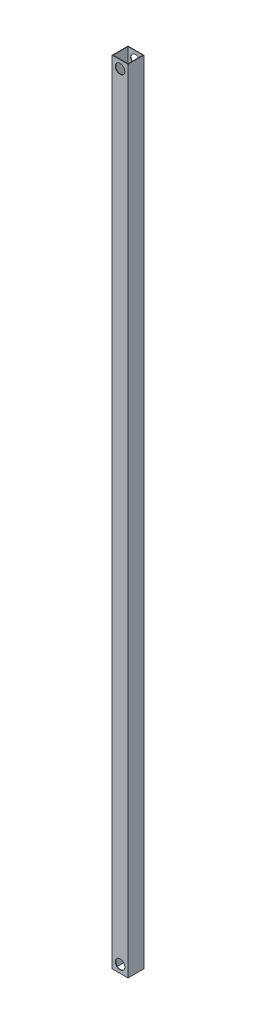
SolidWorks part; units mm, degrees
ref_plane "Alzado" through (0, 0, 0) normal (0, 0, 1) x (1, 0, 0)
ref_plane "Planta" through (0, 0, 0) normal (0, 1, 0) x (1, 0, 0)
ref_plane "Vista lateral" through (0, 0, 0) normal (1, 0, 0) x (0, 0, -1)
sketch "Croquis1" plane through (0, 0, 0) normal (0, 1, 0) x (1, 0, 0)
  line L1 (-5, 5) -> (5, 5)
  line L2 (-5, 5) -> (-5, -5)
  line L3 (-5, -5) -> (5, -5)
  line L4 (5, 5) -> (5, -5)
  line L5 (-5, 5) -> (5, -5) construction
  line L6 (-5, -5) -> (5, 5) construction
  point P0 (0, 0)
  dimension "D1" = 10
  dimension "D2" = 10
extrude "Saliente-Extruir1" add sketch "Croquis1" along normal blind 500
sketch "Croquis2" plane through (0, 500, 0) normal (0, 1, 0) x (1, 0, 0)
  line L0 (-5, 5) -> (-5, -5) construction
  line L1 (-4.683, 4.683) -> (4.683, 4.683)
  line L2 (-4.683, 4.683) -> (-4.683, -4.683)
  line L3 (-4.683, -4.683) -> (4.683, -4.683)
  line L4 (4.683, 4.683) -> (4.683, -4.683)
  line L5 (-4.683, 4.683) -> (4.683, -4.683) construction
  line L6 (-4.683, -4.683) -> (4.683, 4.683) construction
  line L7 (5, 5) -> (-5, 5) construction
  point P0 (0, 0)
  dimension "D1" = 0.317
  dimension "D2" = 0.317
extrude "Cortar-Extruir1" cut sketch "Croquis2" against normal blind 500
sketch "Croquis3" plane through (0, 0, 5) normal (0, 0, 1) x (1, 0, 0)
  line L0 (-5, 10) -> (5, 10) construction
  line L1 (-5, 500) -> (-5, 0) construction
  line L2 (5, 500) -> (5, 0) construction
  line L3 (-5, 0) -> (5, 0) construction
  line L4 (0, 0) -> (0, 10) construction
  line L5 (-5, 5) -> (5, 5) construction
  circle A0 centre (0, 5) radius 3
  dimension "D3" = 6
  dimension "D1" = 10
  dimension "D2" = 5
extrude "Cortar-Extruir2" cut sketch "Croquis3" against normal blind 500
sketch "Croquis4" plane through (0, 0, 5) normal (0, 0, 1) x (1, 0, 0)
  line L0 (5, 490) -> (-5, 490) construction
  line L1 (5, 500) -> (5, 0) construction
  line L2 (-5, 500) -> (-5, 0) construction
  line L3 (5, 495) -> (-5, 495) construction
  line L4 (5, 500) -> (-5, 500) construction
  line L5 (0, 500) -> (0, 490) construction
  circle A0 centre (0, 495) radius 3
  dimension "D3" = 6
  dimension "D1" = 10
  dimension "D2" = 5
extrude "Cortar-Extruir3" cut sketch "Croquis4" against normal blind 500
